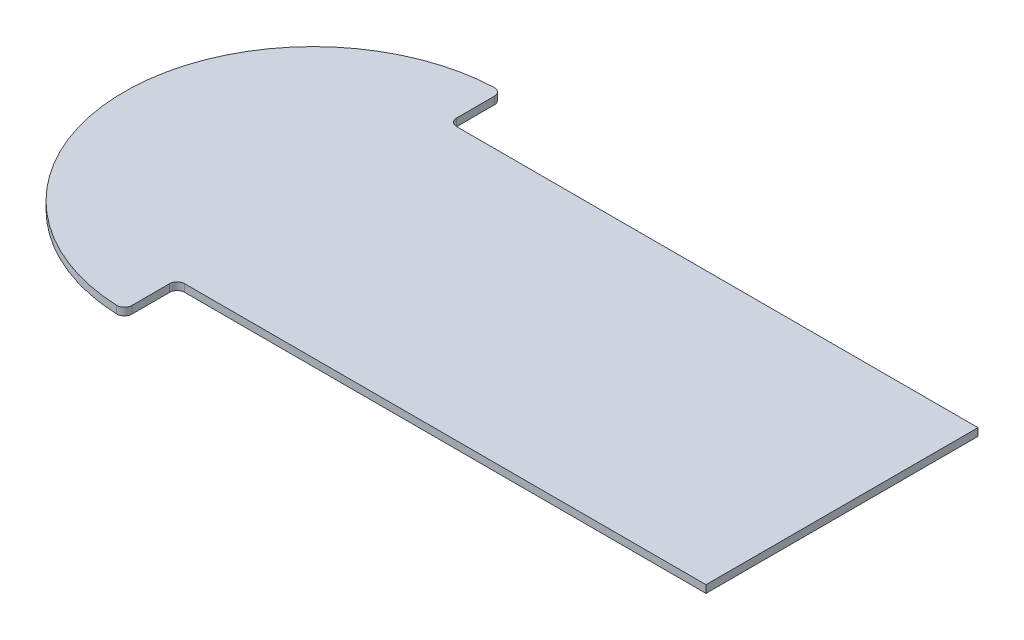
SolidWorks part; units mm, degrees
ref_plane "Front Plane" through (0, 0, 0) normal (0, 0, 1) x (1, 0, 0)
ref_plane "Top Plane" through (0, 0, 0) normal (0, 1, 0) x (1, 0, 0)
ref_plane "Right Plane" through (0, 0, 0) normal (1, 0, 0) x (0, 0, -1)
sketch "Sketch1" plane through (0, 0, 0) normal (0, 1, 0) x (1, 0, 0)
  line L0 (-35, 25) -> (-35, 18)
  line L1 (35, -18) -> (-35, -18)
  line L2 (35, -18) -> (35, 18)
  line L3 (35, 18) -> (-35, 18)
  line L4 (-35, -18) -> (-35, 18)
  line L5 (35, -18) -> (-35, 18) construction
  line L6 (35, 18) -> (-35, -18) construction
  line L7 (-35, -25) -> (-35, -18)
  arc A0 (-35, 25) -> (-35, -25) centre (-35, 0) ccw
  point P0 (0, 0)
  point P9 (-53.9831, 3.168)
  dimension "D3" = 25
  dimension "D1" = 36
  dimension "D2" = 70
extrude "Boss-Extrude1" add sketch "Sketch1" along normal blind 1 contours L0 A0 L7 L4 | L4 L1 L2 L3
fillet "Fillet1" radius 1 4 edges at (-35, 0.5, 18) (-35, 0.5, -18) (-35, 0.5, -25) (-35, 0.5, 25)
